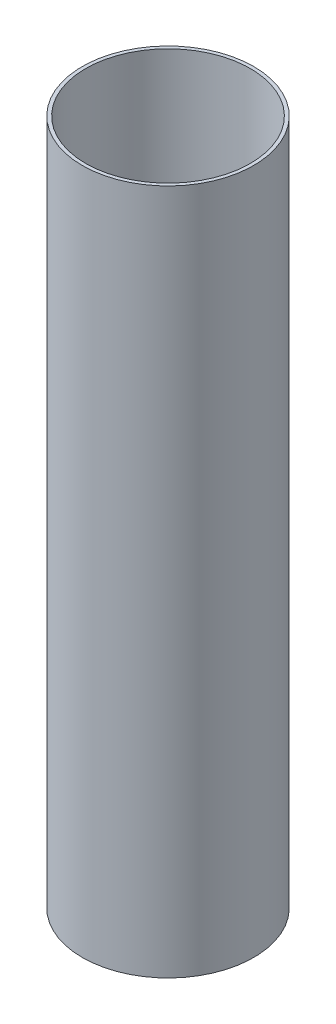
SolidWorks part; units mm, degrees
ref_plane "Front Plane" through (0, 0, 0) normal (0, 0, 1) x (1, 0, 0)
ref_plane "Top Plane" through (0, 0, 0) normal (0, 1, 0) x (1, 0, 0)
ref_plane "Right Plane" through (0, 0, 0) normal (1, 0, 0) x (0, 0, -1)
sketch "Sketch1" plane through (0, 0, 0) normal (0, 1, 0) x (1, 0, 0)
  circle A0 centre (0, 0) radius 50
  circle A1 centre (0, 0) radius 48
  dimension "D1" = 100
  dimension "D2" = 2
extrude "Boss-Extrude1" add sketch "Sketch1" along normal blind 400
